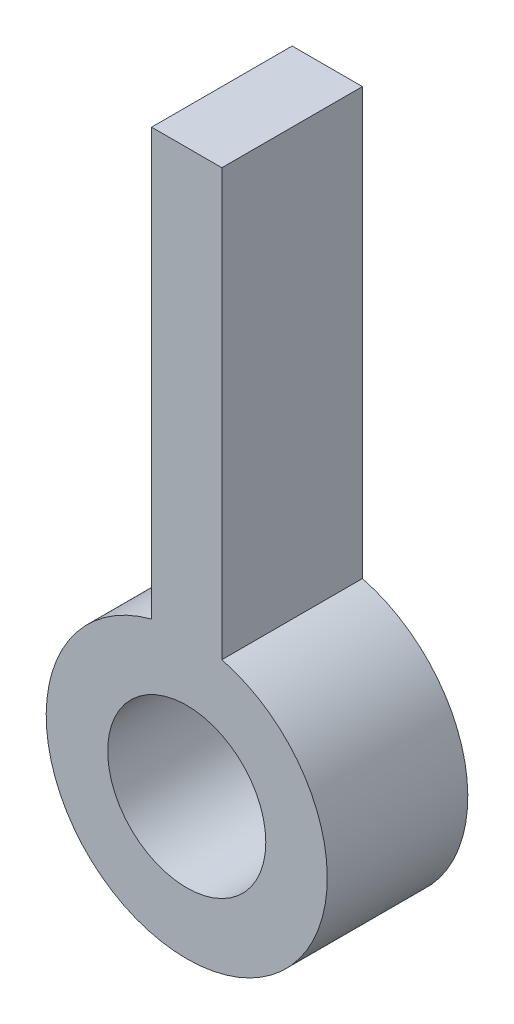
SolidWorks part; units mm, degrees
ref_plane "Front Plane" through (0, 0, 0) normal (1, 0, 0) x (0, 1, 0)
ref_plane "Top Plane" through (0, 0, 0) normal (0, 0, 1) x (0, 1, 0)
ref_plane "Right Plane" through (0, 0, 0) normal (0, 1, 0) x (-1, 0, 0)
sketch "Sketch2" plane through (0, 0, 0) normal (0, 0, 1) x (0, 1, 0)
  line L6 (3.873, 1) -> (16, 1)
  line L8 (3.873, -1) -> (16, -1)
  line L9 (16, 1) -> (16, -1)
  circle A3 centre (0, 0) radius 2.25
  arc A4 (3.873, 1) -> (3.873, -1) centre (0, 0) ccw
  dimension "D1" = 4.5
  dimension "D2" = 8
  dimension "D3" = 12.127
  dimension "D4" = 2
  dimension "D6" = 16
extrude "Boss-Extrude2" add sketch "Sketch2" along normal blind 4
